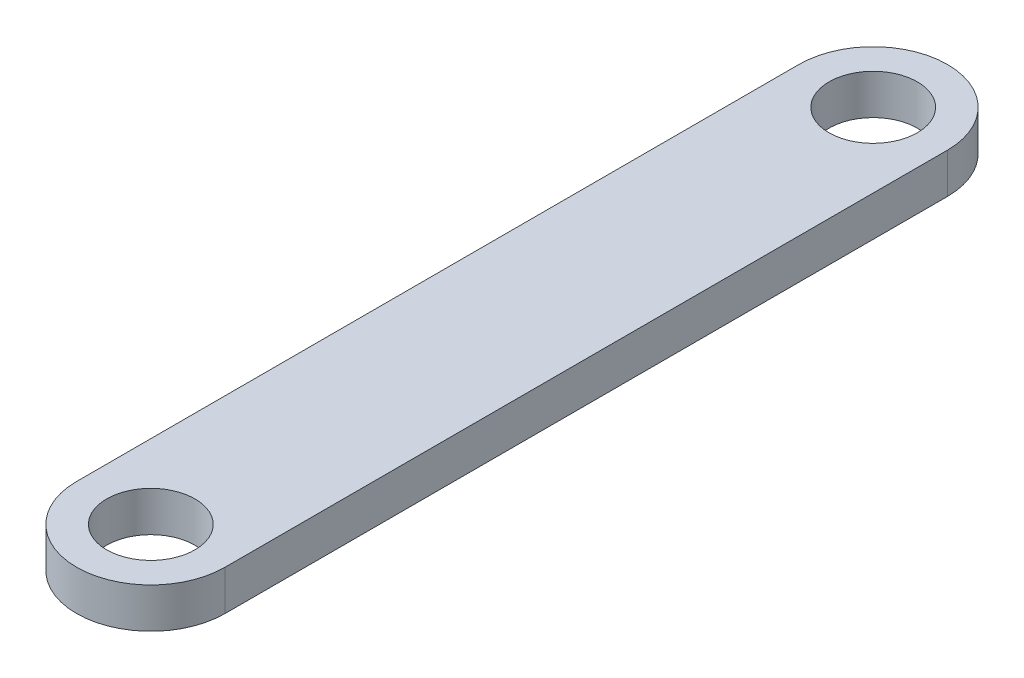
SolidWorks part; units mm, degrees
ref_plane "Front Plane" through (0, 0, 0) normal (0, 0, 1) x (1, 0, 0)
ref_plane "Top Plane" through (0, 0, 0) normal (0, 1, 0) x (1, 0, 0)
ref_plane "Right Plane" through (0, 0, 0) normal (1, 0, 0) x (0, 0, -1)
sketch "Sketch1" plane through (0, 0, 0) normal (0, 1, 0) x (1, 0, 0)
  line L0 (0, 0) -> (49.1133, 0) construction
  line L1 (-18.5, -90) -> (18.5, -90)
  line L2 (-18.5, -90) -> (-18.5, 90)
  line L3 (-18.5, 90) -> (18.5, 90)
  line L4 (18.5, -90) -> (18.5, 90)
  line L5 (-18.5, -90) -> (18.5, 90) construction
  line L6 (-18.5, 90) -> (18.5, -90) construction
  arc A0 (18.5, 90) -> (-18.5, 90) centre (0, 90) ccw
  circle A1 centre (0, 90) radius 4 construction
  circle A2 centre (0, 90) radius 11
  arc A3 (18.5, -90) -> (-18.5, -90) centre (0, -90) cw
  circle A4 centre (0, -90) radius 4 construction
  circle A5 centre (0, -90) radius 11
  point P0 (0, 0)
  dimension "D4" = 8
  dimension "D3" = 180
  dimension "D2" = 7.5
  dimension "D5" = 22
extrude "Boss-Extrude1" add sketch "Sketch1" along normal blind 10 contours A2 L3 L2 L1 L4 | A2 L3 A0 | L1 A5 A3
